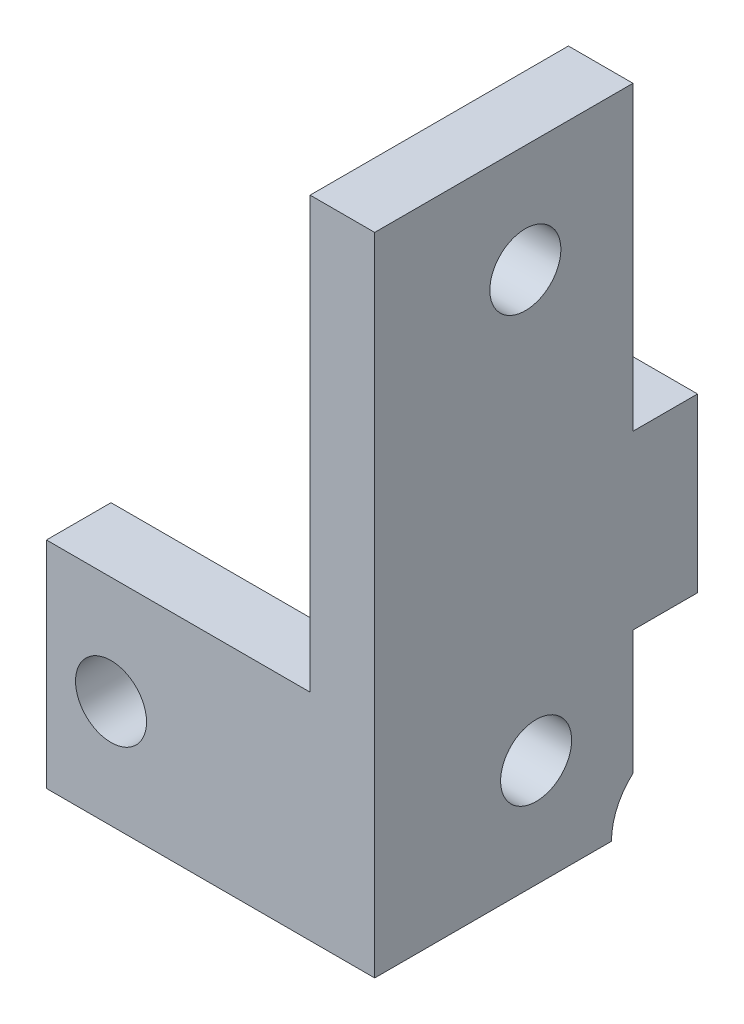
SolidWorks part; units mm, degrees
ref_plane "前视基准面" through (0, 0, 0) normal (0, 0, 1) x (1, 0, 0)
ref_plane "上视基准面" through (0, 0, 0) normal (0, 1, 0) x (1, 0, 0)
ref_plane "右视基准面" through (0, 0, 0) normal (1, 0, 0) x (0, 0, -1)
sketch "草图1" plane through (0, 0, 0) normal (0, 0, 1) x (1, 0, 0)
  line L0 (0, 0) -> (-8.2555, 0) construction
  line L5 (-3, 5) -> (9.25, 5)
  line L6 (-3, 5) -> (-3, -5)
  line L11 (-3, -5) -> (9.25, -5)
  line L12 (9.25, 5) -> (9.25, -5)
  line L13 (0, 0) -> (0, 5) construction
  circle A2 centre (0, 0) radius 1.65
  point P5 (0, 0)
  point P9 (0, 0)
  dimension "D3" = 9.25
  dimension "D1" = 3.3
  dimension "D4" = 3
  dimension "D2" = 10
extrude "凸台-拉伸3" add sketch "草图1" along normal blind 3
sketch "草图3" plane through (0, 0, 3) normal (0, 0, 1) x (1, 0, 0)
  line L1 (9.25, 5) -> (12.25, 5)
  line L2 (9.25, 5) -> (9.25, -5)
  line L3 (9.25, -5) -> (12.25, -5)
  line L4 (12.25, 5) -> (12.25, -5)
  dimension "D1" = 10
  dimension "D2" = 3
extrude "凸台-拉伸4" add sketch "草图3" against normal blind 14
sketch "草图4" plane through (12.25, 0, 0) normal (1, 0, 0) x (0, 0, -1)
  line L0 (0, 5) -> (0, -5)
  line L1 (11, 5) -> (-3, 5) construction
  line L2 (11, -5) -> (-3, -5) construction
  circle A0 centre (4.5, 0) radius 1.65
  point P7 (4.911, 0)
  dimension "D1" = 3.3
  dimension "D2" = 4.5
  dimension "D3" = 5
extrude "切除-拉伸1" cut sketch "草图4" against normal blind 10
sketch "草图6" plane through (12.25, 0, 0) normal (1, 0, 0) x (0, 0, -1)
  line L0 (11, -5) -> (11, 5) construction
  line L1 (-3, 5) -> (11, 5)
  line L2 (-3, 5) -> (-3, 25)
  line L3 (-3, 25) -> (11, 25)
  line L4 (11, 5) -> (11, 25)
  line L5 (-3, 20) -> (11, 20) construction
  circle A0 centre (4, 20) radius 1.65
  point P13 (4, 20)
  dimension "D2" = 3.3
  dimension "D1" = 20
  dimension "D3" = 5
extrude "凸台-拉伸5" add sketch "草图6" against normal blind 3
sketch "草图7" plane through (12.25, 0, 0) normal (1, 0, 0) x (0, 0, -1)
  line L0 (11, -5) -> (-3, -5) construction
  line L1 (11, -5) -> (11, 25) construction
  line L2 (8, -5) -> (11, -5)
  line L3 (11, -5) -> (11, -2)
  arc A0 (8, -5) -> (11, -2) centre (11, -5) cw
  dimension "D2" = 3
  dimension "D1" = 3
extrude "切除-拉伸2" cut sketch "草图7" against normal blind 3
sketch "草图8" plane through (12.25, 0, 0) normal (1, 0, 0) x (0, 0, -1)
  line L1 (11, 25) -> (9, 25)
  line L2 (11, 25) -> (11, -2.7639)
  line L3 (11, -2.7639) -> (9, -2.7639)
  line L4 (9, 25) -> (9, -2.7639)
  arc A0 (11, -2) -> (8, -5) centre (11, -5) ccw construction
  dimension "D1" = 2
extrude "切除-拉伸3" cut sketch "草图8" against normal up to next
sketch "草图9" plane through (12.25, 0, 0) normal (1, 0, 0) x (0, 0, -1)
  line L0 (9, 25) -> (9, -2.7639) construction
  line L1 (9, 11) -> (12, 11)
  line L2 (9, 11) -> (9, 3)
  line L3 (9, 3) -> (12, 3)
  line L4 (12, 11) -> (12, 3)
  circle A0 centre (4, 20) radius 1.65 construction
  dimension "D3" = 8
  dimension "D1" = 3
  dimension "D2" = 9
extrude "凸台-拉伸6" add sketch "草图9" against normal blind 15
